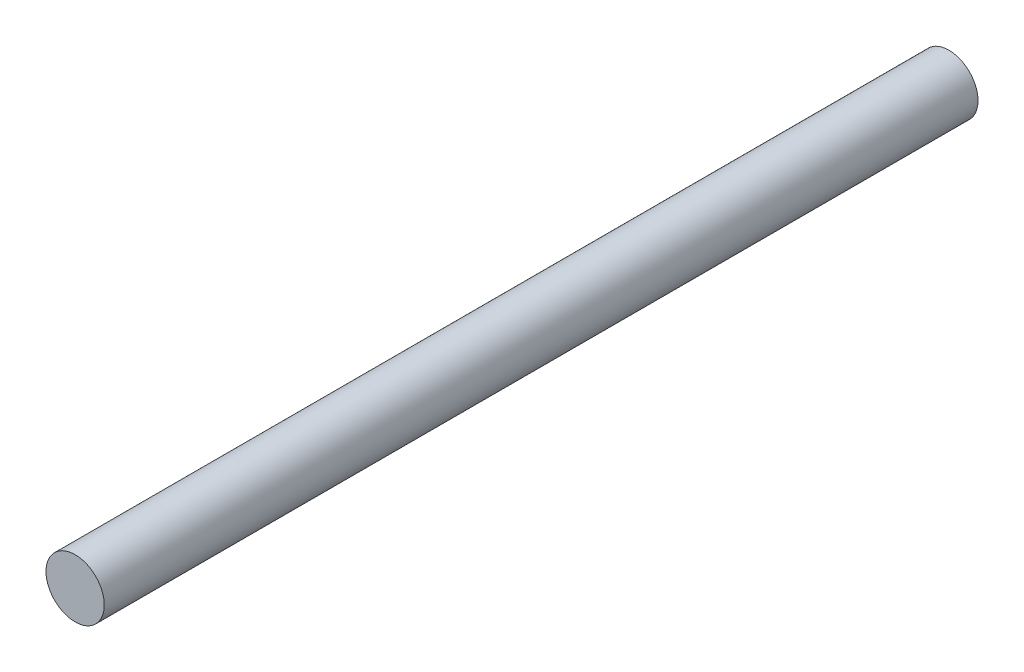
SolidWorks part; units mm, degrees
ref_plane "Front Plane" through (0, 0, 0) normal (0, 0, 1) x (1, 0, 0)
ref_plane "Top Plane" through (0, 0, 0) normal (0, 1, 0) x (1, 0, 0)
ref_plane "Right Plane" through (0, 0, 0) normal (1, 0, 0) x (0, 0, -1)
sketch "Sketch1" plane through (0, 0, 0) normal (0, 0, 1) x (1, 0, 0)
  circle A0 centre (0, 0) radius 6
  dimension "D1" = 12
extrude "Boss-Extrude1" add sketch "Sketch1" along normal blind 180
